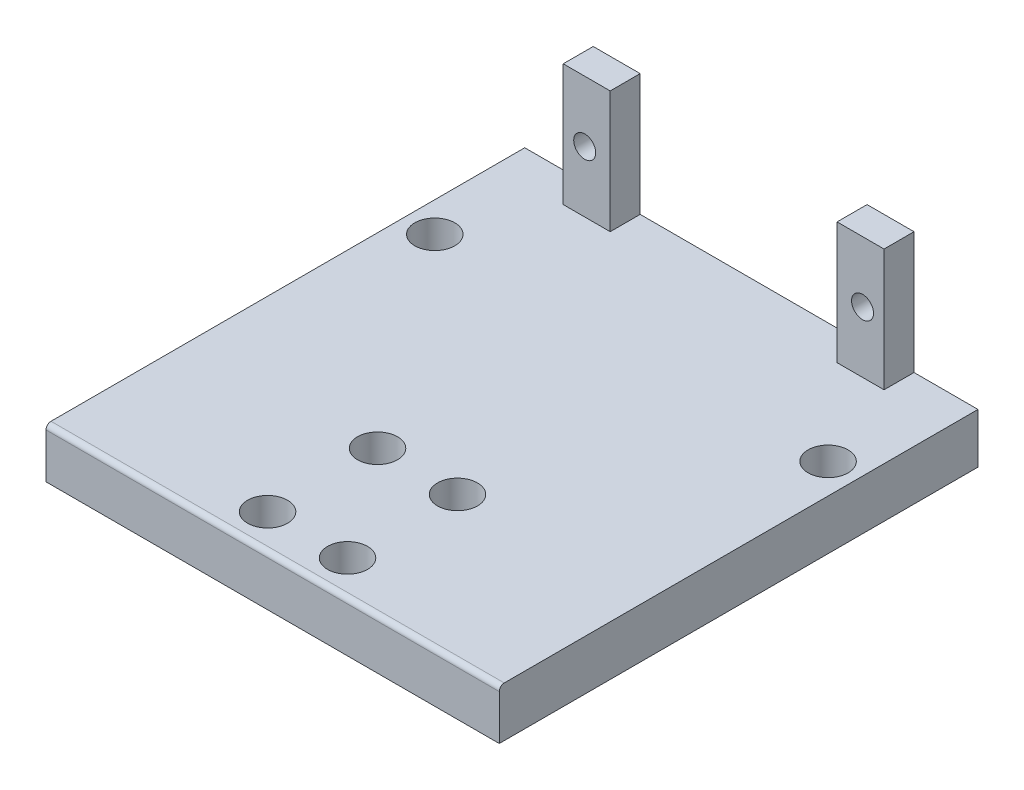
SolidWorks part; units mm, degrees
ref_plane "Front Plane" through (0, 0, 0) normal (0, 0, 1) x (1, 0, 0)
ref_plane "Top Plane" through (0, 0, 0) normal (0, 1, 0) x (1, 0, 0)
ref_plane "Right Plane" through (0, 0, 0) normal (1, 0, 0) x (0, 0, -1)
sketch "Sketch1" plane through (0, 0, 0) normal (0, 0, 1) x (1, 0, 0)
  line L0 (0, 0) -> (0, 56)
  line L1 (0, 56) -> (75.6, 56)
  line L2 (75.6, 56) -> (75.6, 0)
  line L3 (75.6, 0) -> (70.6, 0)
  line L4 (70.6, 0) -> (70.6, 51)
  line L5 (70.6, 51) -> (5, 51)
  line L6 (5, 51) -> (5, 0)
  line L7 (5, 0) -> (0, 0)
  dimension "D1" = 5
  dimension "D2" = 75.6
  dimension "D3" = 5
  dimension "D4" = 5
  dimension "D5" = 56
extrude "Boss-Extrude1" add sketch "Sketch1" along normal blind 47.9
sketch "Sketch4" plane through (0, 0, 0) normal (0, -1, 0) x (1, 0, 0)
  line L1 (-6.946, 52.7093) -> (84.5495, 52.7093)
  line L2 (-6.946, 52.7093) -> (-6.946, -4.3084)
  line L3 (-6.946, -4.3084) -> (84.5495, -4.3084)
  line L4 (84.5495, 52.7093) -> (84.5495, -4.3084)
extrude "Cut-Extrude3" cut sketch "Sketch4" against normal blind 20
sketch "Sketch6" plane through (0, 56, 0) normal (0, 1, 0) x (1, 0, 0)
  line L0 (26.9, 0) -> (26.9, -4.3)
  line L1 (75.6, 0) -> (0, 0) construction
  line L2 (26.9, -4.3) -> (22.1, -4.3)
  line L3 (22.1, -4.3) -> (22.1, -6.8)
  line L4 (22.1, -6.8) -> (26.9, -6.8)
  line L5 (26.9, -6.8) -> (26.9, -22.5)
  line L6 (26.9, -22.5) -> (49.4, -22.5)
  line L7 (49.4, -22.5) -> (49.4, -6.8)
  line L8 (49.4, -6.8) -> (54.2, -6.8)
  line L9 (54.2, -6.8) -> (54.2, -4.3)
  line L10 (54.2, -4.3) -> (49.4, -4.3)
  line L11 (49.4, -4.3) -> (49.4, 0)
  line L12 (49.4, 0) -> (26.9, 0)
  line L15 (0, -47.9) -> (0, 0) construction
  line L16 (51.4, 0) -> (51.4, -2.3)
  line L17 (51.4, -2.3) -> (56.2, -2.3)
  line L18 (56.2, -2.3) -> (56.2, -8.8)
  line L19 (56.2, -8.8) -> (51.4, -8.8)
  line L20 (51.4, -8.8) -> (51.4, -24.5)
  line L21 (51.4, -24.5) -> (24.9, -24.5)
  line L22 (24.9, -24.5) -> (24.9, -8.8)
  line L23 (24.9, -8.8) -> (20.1, -8.8)
  line L24 (20.1, -8.8) -> (20.1, -2.3)
  line L25 (20.1, -2.3) -> (24.9, -2.3)
  line L26 (24.9, -2.3) -> (24.9, 0)
  line M7 (75.6, 0) -> (0, 0)
  dimension "D1" = 26.9
  dimension "D2" = 4.8
  dimension "D3" = 4.8
  dimension "D4" = 4.8
  dimension "D5" = 4.8
  dimension "D6" = 22.5
  dimension "D7" = 4.3
  dimension "D8" = 4.3
  dimension "D9" = 22.5
  dimension "D10" = 2.5
  dimension "D11" = 2.5
  dimension "D12" = 2
  dimension "D13" = 2
  dimension "D14" = 2
  dimension "D15" = 2
  dimension "D16" = 2
  dimension "D17" = 2
  dimension "D18" = 2
  dimension "D19" = 2
  dimension "D20" = 2
  dimension "D21" = 2
  dimension "D22" = 2
extrude "Boss-Extrude2" add sketch "Sketch6" along normal blind 3 contours L26 L25 L24 L23 L22 L21 L20 L19 L18 L17 L16 L11 L10 L9 L8 L7 L6 L5 L4 L3 L2 L0 M7
fillet "Fillet1" radius 0.5 18 edges at (51.4, 57.5, 0) (24.9, 57.5, 0) (20.1, 56, 5.55) (22.5, 56, 8.8) (24.9, 56, 16.65) (38.15, 56, 24.5) (51.4, 56, 16.65) (53.8, 56, 8.8) (56.2, 56, 5.55) (53.8, 56, 2.3) (51.4, 56, 1.15) (63.5, 56, 0) (75.6, 56, 23.95) (37.8, 56, 47.9) (0, 56, 23.95) (12.45, 56, 0) (24.9, 56, 1.15) (22.5, 56, 2.3)
sketch "Sketch7" plane through (0, 20, 0) normal (0, -1, 0) x (1, 0, 0)
  line L1 (0, 47.9) -> (5, 47.9)
  line L2 (0, 47.9) -> (0, 0)
  line L3 (0, 0) -> (5, 0)
  line L4 (5, 47.9) -> (5, 0)
  line L5 (70.6, 47.9) -> (75.6, 47.9)
  line L6 (70.6, 47.9) -> (70.6, 0)
  line L7 (70.6, 0) -> (75.6, 0)
  line L8 (75.6, 47.9) -> (75.6, 0)
extrude "Cut-Extrude4" cut sketch "Sketch7" against normal up to surface (31 mm away) up to face at (37.8, 51, 23.95)
sketch "Sketch8" plane through (0, 56, 0) normal (0, 1, 0) x (1, 0, 0)
  line L0 (0, 0) -> (24.4, 0) construction
  line L1 (15.25, 0) -> (0.25, 0)
  line L2 (15.25, 0) -> (15.25, -47.65)
  line L3 (15.25, -47.65) -> (0.25, -47.65)
  line L4 (0.25, 0) -> (0.25, -47.65)
  line L5 (0.5, -47.4) -> (0, -47.9) construction
  line L6 (75.6, -47.9) -> (0, -47.9) construction
  line L7 (75.6, 0) -> (60.6, 0)
  line L8 (75.6, 0) -> (75.6, -47.9)
  line L9 (75.6, -47.9) -> (60.6, -47.9)
  line L10 (60.6, 0) -> (60.6, -47.9)
  line L12 (0, 0) -> (15.25, 0)
  line L13 (0, 0) -> (0, -47.9)
  line L14 (0, -47.9) -> (15.25, -47.9)
  line L15 (15.25, 0) -> (15.25, -47.9)
  line M7 (24.4, -0.5) -> (0.5, -0.5)
  line M8 (0.5, -0.5) -> (0.5, -47.4)
  line M9 (0.5, -47.4) -> (75.1, -47.4)
  line M13 (0.5, -47.4) -> (75.1, -47.4)
  line M14 (75.1, -47.4) -> (75.1, -0.5)
  line M15 (75.1, -0.5) -> (51.9, -0.5)
  dimension "D1" = 15
  dimension "D2" = 15
extrude "Cut-Extrude6" cut sketch "Sketch8" against normal through all contours L2 M7 M8 M9 | L15 L3 L4 L12 L13 L14 | L1 L4 L3 L2 M9 M8 M7 | L10 M15 M13 M14 | L7 L10 L9 L8 M15 M14 M13
sketch "Sketch9" plane through (0, 59, 0) normal (0, 1, 0) x (1, 0, 0)
  line L0 (60.6, -0.5) -> (60.6, -47.4) construction
  line L1 (15.25, 0) -> (60.6, 0)
  line L2 (15.25, 0) -> (15.25, -26.396)
  line L3 (15.25, -26.396) -> (60.6, -26.396)
  line L4 (60.6, 0) -> (60.6, -26.396)
extrude "Cut-Extrude7" cut sketch "Sketch9" against normal up to surface (3 mm away) up to face at (38.0938, 56, 11.95)
sketch "Sketch11" plane through (0, 0, 0) normal (0, 0, -1) x (-1, 0, 0)
  line L0 (-51.034, 56) -> (-25.266, 56) construction
  line L1 (-38.15, 56) -> (-22.1, 56)
  line L2 (-38.15, 56) -> (-38.15, 68.2)
  line L3 (-38.15, 68.2) -> (-22.1, 68.2)
  line L4 (-22.1, 56) -> (-22.1, 68.2)
  line L5 (-22.1, 62.1) -> (-54.2, 62.1)
  line L6 (-38.15, 56) -> (-54.2, 56)
  line L7 (-38.15, 56) -> (-38.15, 68.2)
  line L8 (-38.15, 68.2) -> (-54.2, 68.2)
  line L9 (-54.2, 56) -> (-54.2, 68.2)
  circle A0 centre (-52.05, 62.1) radius 1.1
  circle A1 centre (-24.25, 62.1) radius 1.1
  line M1 (-25.266, 56) -> (-51.034, 56)
  dimension "D4" = 2.2
  dimension "D5" = 2.2
  dimension "D1" = 16.05
  dimension "D2" = 16.05
  dimension "D3" = 12.2
  dimension "D6" = 2.15
  dimension "D7" = 2.15
extrude "Boss-Extrude3" add sketch "Sketch11" against normal blind 3 contours A0 L5 L2 L8 L9 | A0 L5 L9 L6 L2 M1 | A1 L5 L4 L3 L2 | A1 L5 L2 L1 L4 M1
sketch "Sketch12" plane through (0, 0, 0) normal (0, 0, -1) x (-1, 0, 0)
  line L0 (-22.1, 68.2) -> (-54.2, 68.2) construction
  line L1 (-49.5, 68.2) -> (-26.8, 68.2)
  line L2 (-49.5, 68.2) -> (-49.5, 56)
  line L3 (-49.5, 56) -> (-26.8, 56)
  line L4 (-26.8, 68.2) -> (-26.8, 56)
  line L5 (-54.2, 56) -> (-54.2, 68.2) construction
  line L6 (-22.1, 56) -> (-22.1, 68.2) construction
  dimension "D1" = 4.7
  dimension "D2" = 4.7
extrude "Cut-Extrude8" cut sketch "Sketch12" against normal through all
sketch "Sketch13" plane through (0, 0, 0) normal (0, 0, -1) x (-1, 0, 0)
  line L1 (-60.6, 51) -> (-15.25, 51)
  line L2 (-60.6, 51) -> (-60.6, 56)
  line L3 (-60.6, 56) -> (-15.25, 56)
  line L4 (-15.25, 51) -> (-15.25, 56)
extrude "Boss-Extrude4" add sketch "Sketch13" against normal blind 3
sketch "Sketch16" plane through (0, 56, 0) normal (0, 1, 0) x (1, 0, 0)
  line L1 (15.25, 0) -> (15.25, -47.4) construction
  circle A0 centre (33.925, -33.4047) radius 2
  circle A1 centre (41.925, -33.4047) radius 2
  circle A2 centre (41.925, -44.4047) radius 2
  circle A3 centre (33.925, -44.4047) radius 2
  dimension "D5" = 4
  dimension "D1" = 11
  dimension "D2" = 11
  dimension "D3" = 8
  dimension "D4" = 18.675
extrude "Cut-Extrude9" cut sketch "Sketch16" against normal blind 10
sketch "Sketch18" plane through (0, 56, 0) normal (0, 1, 0) x (1, 0, 0)
  line L0 (15.25, 0) -> (22.1, 0) construction
  line L1 (15.25, 0) -> (15.25, -47.4) construction
  line L2 (60.6, 0) -> (60.6, -47.4) construction
  line L3 (54.2, 0) -> (60.6, 0) construction
  circle A0 centre (18.25, -12) radius 2
  circle A1 centre (57.6, -12) radius 2
  dimension "D1" = 4
  dimension "D2" = 4
  dimension "D3" = 12
  dimension "D4" = 3
  dimension "D5" = 3
  dimension "D6" = 12
extrude "Cut-Extrude10" cut sketch "Sketch18" against normal blind 10
equation "\"D4@Sketch16\"=37.35/2"
